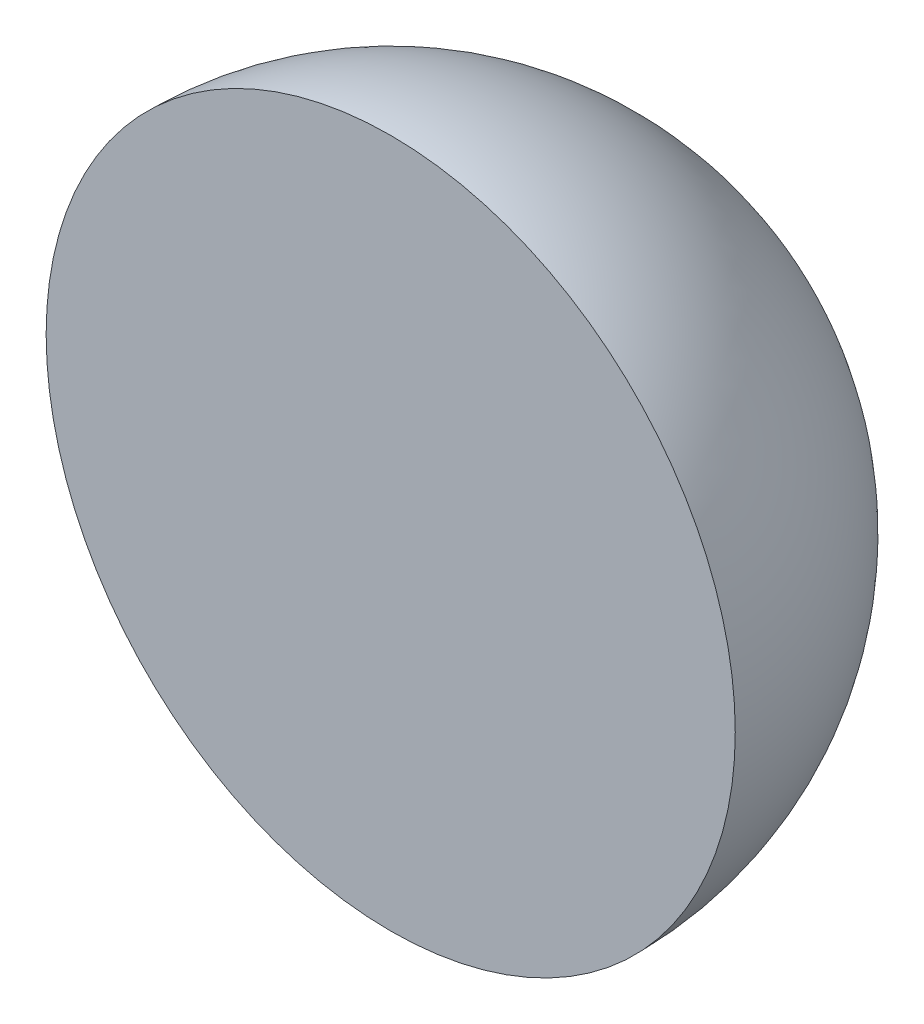
SolidWorks part; units mm, degrees
ref_plane "Front Plane" through (0, 0, 0) normal (0, 0, 1) x (1, 0, 0)
ref_plane "Top Plane" through (0, 0, 0) normal (0, 1, 0) x (1, 0, 0)
ref_plane "Right Plane" through (0, 0, 0) normal (1, 0, 0) x (0, 0, -1)
sketch "Sketch1" plane through (0, 0, 0) normal (0, 1, 0) x (1, 0, 0)
  line L0 (0, 197.8876) -> (0, 0)
  line L1 (0, 0) -> (197.8876, 0)
  arc A0 (197.8876, 0) -> (0, 197.8876) centre (0, 0) ccw
  point P4 (197.8876, 0)
  point P6 (0, 197.8876)
revolve "Revolve2" add sketch "Sketch1" angle 360 about L0
